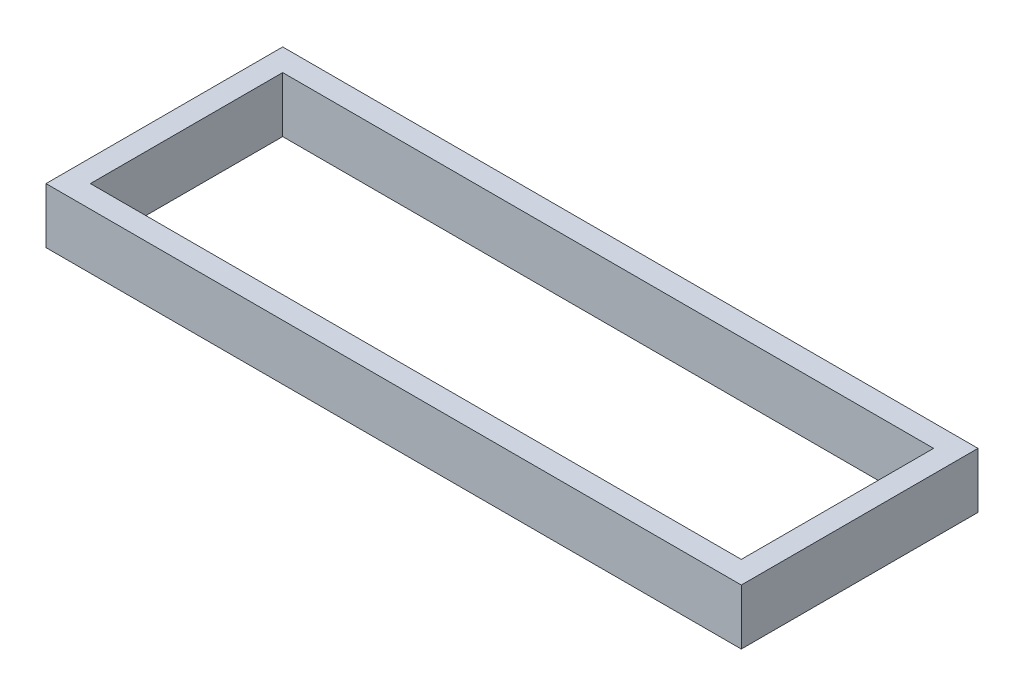
SolidWorks part; units mm, degrees
ref_plane "Front Plane" through (0, 0, 0) normal (0, 0, 1) x (1, 0, 0)
ref_plane "Top Plane" through (0, 0, 0) normal (0, 1, 0) x (1, 0, 0)
ref_plane "Right Plane" through (0, 0, 0) normal (1, 0, 0) x (0, 0, -1)
sketch "Sketch1" plane through (0, 0, 0) normal (0, 1, 0) x (1, 0, 0)
  line L0 (-94, -32) -> (-94, 32)
  line L1 (-88, -26) -> (88, -26)
  line L2 (-88, -26) -> (-88, 26)
  line L3 (-88, 26) -> (88, 26)
  line L4 (88, -26) -> (88, 26)
  line L5 (-88, -26) -> (88, 26) construction
  line L6 (-88, 26) -> (88, -26) construction
  line L11 (-94, 32) -> (94, 32)
  line L12 (94, -32) -> (94, 32)
  line L13 (-94, -32) -> (94, -32)
  point P0 (0, 0)
  point P6 (0, 0)
  dimension "D1" = 176
  dimension "D2" = 52
  dimension "D3" = 6
extrude "Boss-Extrude1" add sketch "Sketch1" along normal blind 15
